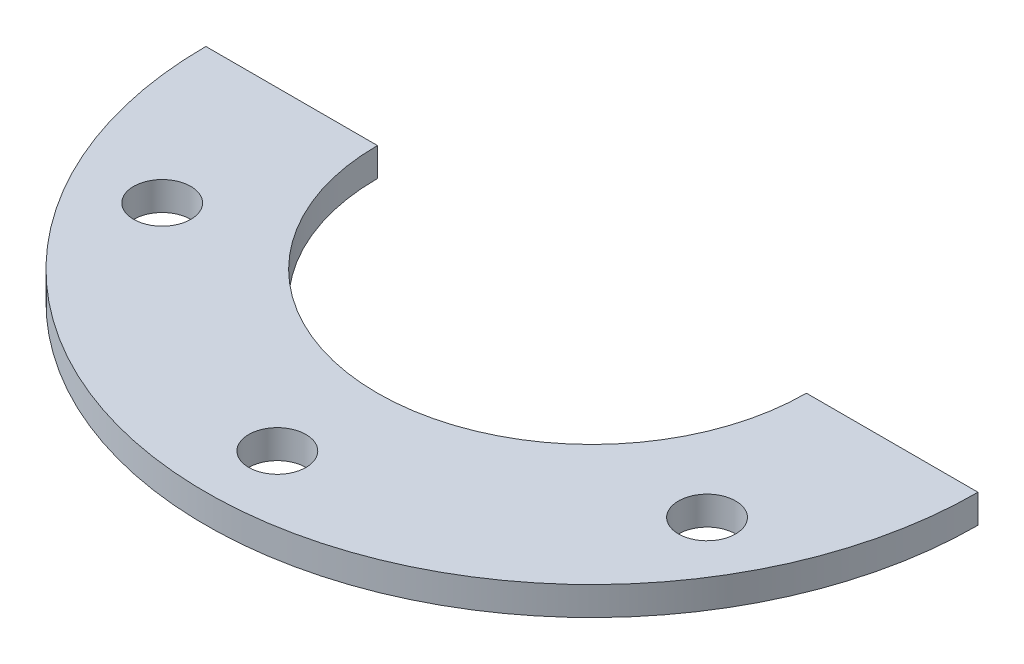
SolidWorks part; units mm, degrees
material "ABS"
ref_plane "Front Plane" through (0, 0, 0) normal (0, 0, 1) x (1, 0, 0)
ref_plane "Top Plane" through (0, 0, 0) normal (0, 1, 0) x (1, 0, 0)
ref_plane "Right Plane" through (0, 0, 0) normal (1, 0, 0) x (0, 0, -1)
sketch "Sketch1" plane through (0, 0, 0) normal (0, 1, 0) x (1, 0, 0)
  circle A0 centre (0, 0) radius 13.5
  dimension "D1" = 27
extrude "Boss-Extrude1" add sketch "Sketch1" along normal blind 1
sketch "Sketch19" plane through (0, 1, 0) normal (0, 1, 0) x (1, 0, 0)
  circle A0 centre (0, 11) radius 1
  circle A1 centre (9.5263, 5.5) radius 1
  circle A2 centre (9.5263, -5.5) radius 1
  circle A3 centre (0, -11) radius 1
  circle A4 centre (-9.5263, -5.5) radius 1
  circle A5 centre (-9.5263, 5.5) radius 1
  point P13 (0, 0)
  dimension "D1" = 2
  dimension "D2" = 11
  dimension "D3" = 6
extrude "Cut-Extrude1" cut sketch "Sketch19" against normal through all both and the other way through all
sketch "Sketch20" plane through (0, 1, 0) normal (0, 1, 0) x (1, 0, 0)
  circle A0 centre (0, 0) radius 7.5
  dimension "D1" = 15
extrude "Cut-Extrude2" cut sketch "Sketch20" against normal through all both and the other way through all
sketch "Sketch21" plane through (0, 0, 0) normal (0, 0, 1) x (1, 0, 0)
  line L1 (-36.7533, 32.3113) -> (29.1209, 32.3113)
  line L2 (-36.7533, 32.3113) -> (-36.7533, -19.668)
  line L3 (-36.7533, -19.668) -> (29.1209, -19.668)
  line L4 (29.1209, 32.3113) -> (29.1209, -19.668)
extrude "Cut-Extrude3" cut sketch "Sketch21" against normal through all
